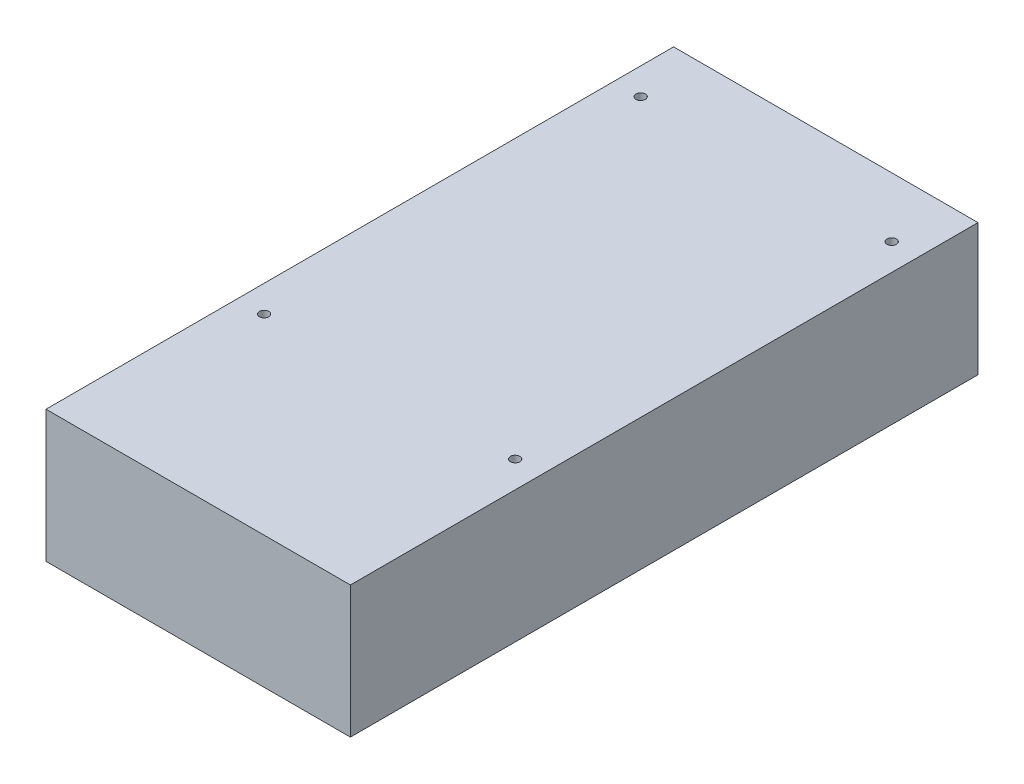
SolidWorks part; units mm, degrees
ref_plane "Front Plane" through (0, 0, 0) normal (0, 0, 1) x (1, 0, 0)
ref_plane "Top Plane" through (0, 0, 0) normal (0, 1, 0) x (1, 0, 0)
ref_plane "Right Plane" through (0, 0, 0) normal (1, 0, 0) x (0, 0, -1)
sketch "Sketch1" plane through (0, 0, 0) normal (0, 1, 0) x (1, 0, 0)
  line L1 (0, 0) -> (97, 0)
  line L2 (0, 0) -> (0, 200)
  line L3 (0, 200) -> (97, 200)
  line L4 (97, 0) -> (97, 200)
  dimension "D1" = 97
  dimension "D2" = 200
extrude "Boss-Extrude1" add sketch "Sketch1" along normal blind 42
sketch "Sketch3" plane through (0, 42, 0) normal (0, 1, 0) x (1, 0, 0)
  line L0 (0, 0) -> (97, 0) construction
  line L1 (97, 0) -> (97, 200) construction
  circle A0 centre (88.5, 61) radius 1.5
  circle A1 centre (8.5, 61) radius 1.5
  circle A2 centre (88.5, 181) radius 1.5
  circle A3 centre (8.5, 181) radius 1.5
  point P12 (0, 0)
  point P13 (0, 0)
  point P14 (0, 0)
  dimension "D1" = 3
  dimension "D2" = 61
  dimension "D3" = 8.5
  dimension "D4" = 80
  dimension "D5" = 61
  dimension "D6" = 120
  dimension "D7" = 120
extrude "Cut-Extrude1" cut sketch "Sketch3" against normal blind 3
